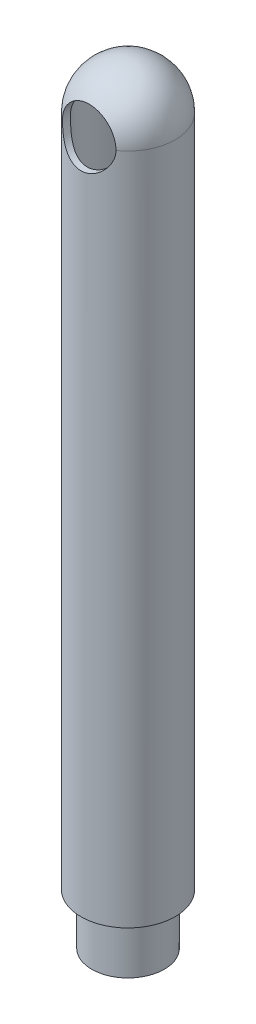
SolidWorks part; units mm, degrees
ref_plane "Plano frontal" through (0, 0, 0) normal (0, 0, 1) x (1, 0, 0)
ref_plane "Plano superior" through (0, 0, 0) normal (0, 1, 0) x (1, 0, 0)
ref_plane "Plano direito" through (0, 0, 0) normal (1, 0, 0) x (0, 0, -1)
sketch "Sketch1" plane through (0, 0, 0) normal (0, 0, 1) x (1, 0, 0)
  line L0 (0, 0) -> (0, 893.401) construction
  line L1 (28.5, 0) -> (28.5, 40)
  line L2 (28.5, 40) -> (37, 40)
  line L3 (37, 40) -> (37, 568)
  line L4 (23.5, 0) -> (23.5, 45)
  line L5 (23.5, 45) -> (32, 45)
  line L6 (32, 45) -> (32, 821)
  line L7 (28.5, 0) -> (23.5, 0)
  line L8 (32, 45) -> (32, 568) construction
  line L9 (0, 605) -> (0, 600)
  arc A0 (37, 568) -> (0, 605) centre (0, 568) ccw
  arc A1 (32, 568) -> (0, 600) centre (0, 568) ccw
  dimension "D6" = 37
  dimension "D1" = 57
  dimension "D2" = 40
  dimension "D3" = 74
  dimension "D5" = 528
  dimension "D4" = 5
  dimension "D7" = 5
revolve "Revolve1" add sketch "Sketch1" angle 360 about L0
sketch "Sketch2" plane through (0, 0, 0) normal (0, 0, 1) x (1, 0, 0)
  line L0 (37, 568) -> (-37, 568) construction
  circle A0 centre (0, 568) radius 21
  dimension "D1" = 42
extrude "Cut-Extrude1" cut sketch "Sketch2" against normal through all both and the other way through all
